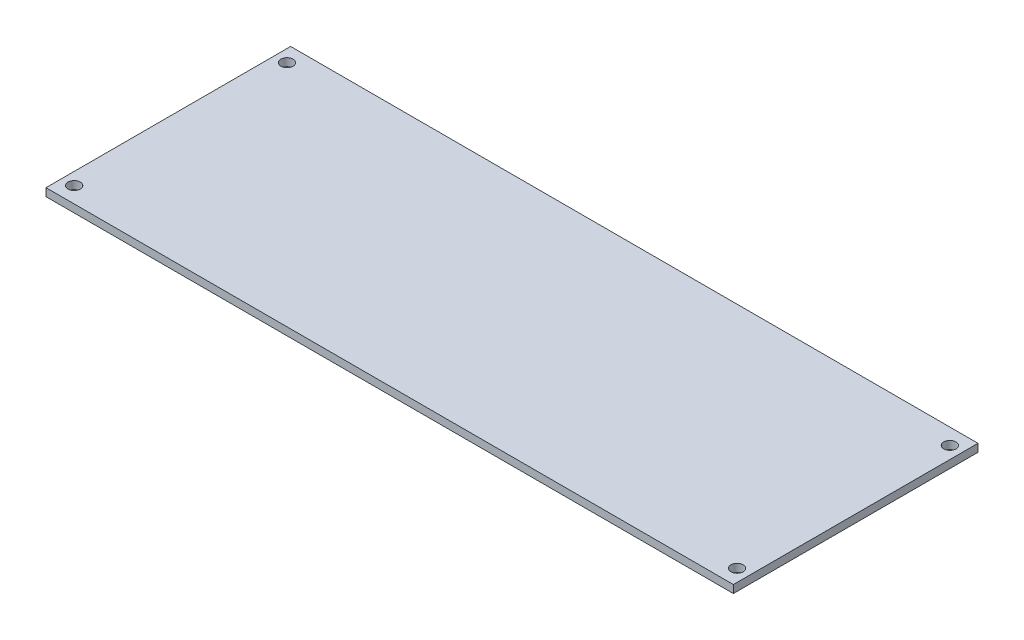
SolidWorks part; units mm, degrees
ref_plane "Front Plane" through (0, 0, 0) normal (0, 0, 1) x (1, 0, 0)
ref_plane "Top Plane" through (0, 0, 0) normal (0, 1, 0) x (1, 0, 0)
ref_plane "Right Plane" through (0, 0, 0) normal (1, 0, 0) x (0, 0, -1)
sketch "Sketch1" plane through (0, 0, 0) normal (0, 1, 0) x (1, 0, 0)
  line L0 (0, 25) -> (0, -25) construction
  line L1 (-70.25, 25) -> (70.25, 25)
  line L2 (-70.25, 25) -> (-70.25, -25)
  line L3 (-70.25, -25) -> (70.25, -25)
  line L4 (70.25, 25) -> (70.25, -25)
  line L5 (-70.25, 25) -> (70.25, -25) construction
  line L6 (-70.25, -25) -> (70.25, 25) construction
  line L7 (-70.25, 0) -> (70.25, 0) construction
  circle A0 centre (-67.75, 21.75) radius 1.25
  circle A1 centre (67.75, 21.75) radius 1.25
  circle A2 centre (67.75, -21.75) radius 1.25
  circle A3 centre (-67.75, -21.75) radius 1.25
  point P0 (0, 0)
  dimension "D5" = 2.5
  dimension "D1" = 140.5
  dimension "D2" = 50
  dimension "D3" = 43.5
  dimension "D4" = 135.5
extrude "Boss-Extrude1" add sketch "Sketch1" along normal blind 1.6
